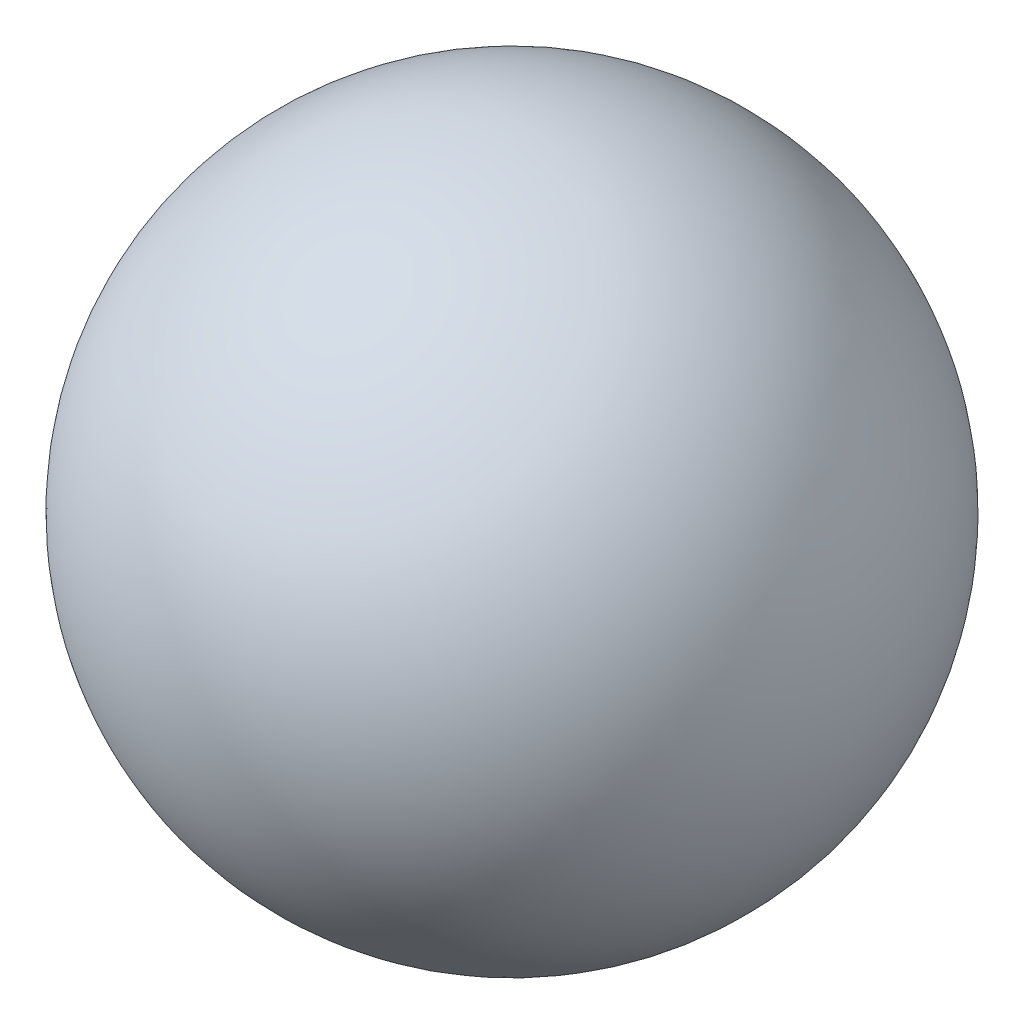
SolidWorks part; units mm, degrees
ref_plane "Front Plane" through (0, 0, 0) normal (0, 0, 1) x (1, 0, 0)
ref_plane "Top Plane" through (0, 0, 0) normal (0, 1, 0) x (1, 0, 0)
ref_plane "Right Plane" through (0, 0, 0) normal (1, 0, 0) x (0, 0, -1)
sketch "Sketch1" plane through (0, 0, 0) normal (0, 1, 0) x (1, 0, 0)
  line L0 (0, 34.25) -> (0, -34.25)
  arc A0 (0, 34.25) -> (0, -34.25) centre (0, 0) cw
  point P2 (-1.0116, 34.5535)
  point P6 (0, 0)
  point P7 (0, -35.1168)
  dimension "D1" = 34.25
revolve "Revolve1" add sketch "Sketch1" angle 360 about L0
